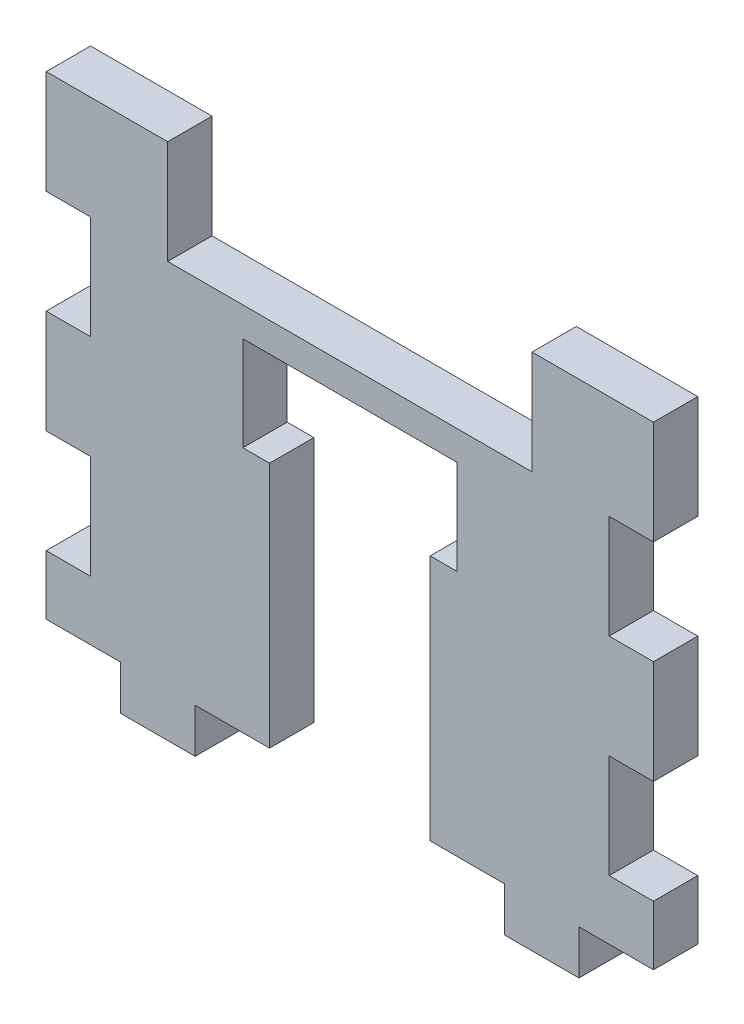
SolidWorks part; units mm, degrees
ref_plane "Front Plane" through (0, 0, 0) normal (0, 0, 1) x (1, 0, 0)
ref_plane "Top Plane" through (0, 0, 0) normal (0, 1, 0) x (1, 0, 0)
ref_plane "Right Plane" through (0, 0, 0) normal (1, 0, 0) x (0, 0, -1)
sketch "Sketch1" plane through (0, 0, 0) normal (0, 0, 1) x (1, 0, 0)
  line L0 (0, 0.2997) -> (31.2293, 0.2997) construction
  line L1 (-31.2293, -26.67) -> (31.2293, -26.67) construction
  line L2 (-31.2293, -26.67) -> (-31.2293, 26.67)
  line L3 (-31.2293, 26.67) -> (31.2293, 26.67)
  line L4 (31.2293, -26.67) -> (31.2293, 26.67)
  line L5 (-31.2293, -26.67) -> (31.2293, 26.67) construction
  line L6 (-31.2293, 26.67) -> (31.2293, -26.67) construction
  line L7 (0, 26.67) -> (0, 0.2997) construction
  line L8 (-31.2293, 26.67) -> (-31.2293, 7.8308) construction
  line L9 (0, 26.67) -> (0, 12.9921) construction
  line L10 (31.2293, 26.67) -> (26.67, 26.67) construction
  line L11 (26.67, 26.67) -> (26.67, -26.67) construction
  line L12 (0, 12.9921) -> (26.67, 12.9921) construction
  line L13 (0, 12.9921) -> (11.0096, 12.9921) construction
  line L14 (11.0096, 12.9921) -> (11.0096, 3.2715)
  line L15 (11.0096, 3.2715) -> (8.2572, 3.2715)
  line L16 (11.0096, 12.9921) -> (-11.0096, 12.9921)
  line L17 (8.2572, 3.2715) -> (8.2572, -26.67)
  line L18 (-11.0096, 12.9921) -> (-11.0096, 3.2715)
  line L19 (8.2572, -26.67) -> (31.2293, -26.67)
  line L20 (-11.0096, 3.2715) -> (-8.2572, 3.2715)
  line L21 (-8.2572, 3.2715) -> (-8.2572, -26.67)
  line L22 (-8.2572, -26.67) -> (-31.2293, -26.67)
  line L23 (15.9146, -22.1107) -> (8.2572, -22.1107)
  line L24 (-31.2293, 26.67) -> (-26.67, 26.67) construction
  line L25 (-31.2293, 26.67) -> (-31.2293, 16.002) construction
  line L26 (-31.2293, 16.002) -> (-26.67, 16.002) construction
  line L27 (-26.67, 26.67) -> (-26.67, 16.002) construction
  line L28 (-26.67, 16.002) -> (-31.2293, 16.002)
  line L29 (-26.67, 16.002) -> (-26.67, 5.334)
  line L30 (-26.67, 5.334) -> (-31.2293, 5.334)
  line L31 (-31.2293, 16.002) -> (-31.2293, 5.334)
  line L32 (-26.67, 5.334) -> (-31.2293, 5.334) construction
  line L33 (-26.67, 5.334) -> (-26.67, -5.334) construction
  line L34 (-26.67, -5.334) -> (-31.2293, -5.334) construction
  line L35 (-31.2293, 5.334) -> (-31.2293, -5.334) construction
  line L36 (-26.67, -5.334) -> (-31.2293, -5.334)
  line L37 (-26.67, -5.334) -> (-26.67, -16.002)
  line L38 (-26.67, -16.002) -> (-31.2293, -16.002)
  line L39 (-31.2293, -5.334) -> (-31.2293, -16.002)
  line L40 (-26.67, -16.002) -> (-31.2293, -16.002) construction
  line L41 (-26.67, -16.002) -> (-26.67, -26.67) construction
  line L42 (-26.67, -26.67) -> (-31.2293, -26.67) construction
  line L43 (-31.2293, -16.002) -> (-31.2293, -26.67) construction
  line L44 (31.2293, 26.67) -> (26.67, 26.67) construction
  line L45 (31.2293, 26.67) -> (31.2293, 16.002) construction
  line L46 (31.2293, 16.002) -> (26.67, 16.002) construction
  line L47 (26.67, 26.67) -> (26.67, 16.002) construction
  line L48 (26.67, 16.002) -> (31.2293, 16.002)
  line L49 (26.67, 16.002) -> (26.67, 5.334)
  line L50 (26.67, 5.334) -> (31.2293, 5.334)
  line L51 (31.2293, 16.002) -> (31.2293, 5.334)
  line L52 (26.67, 5.334) -> (31.2293, 5.334) construction
  line L53 (26.67, 5.334) -> (26.67, -5.334) construction
  line L54 (26.67, -5.334) -> (31.2293, -5.334) construction
  line L55 (31.2293, 5.334) -> (31.2293, -5.334) construction
  line L56 (26.67, -5.334) -> (31.2293, -5.334)
  line L57 (26.67, -5.334) -> (26.67, -16.002)
  line L58 (26.67, -16.002) -> (31.2293, -16.002)
  line L59 (31.2293, -5.334) -> (31.2293, -16.002)
  line L60 (26.67, -16.002) -> (31.2293, -16.002) construction
  line L61 (26.67, -16.002) -> (26.67, -26.67) construction
  line L62 (26.67, -26.67) -> (31.2293, -26.67) construction
  line L63 (31.2293, -16.002) -> (31.2293, -26.67) construction
  line L64 (-31.2293, 26.67) -> (-18.7376, 26.67) construction
  line L65 (-31.2293, 26.67) -> (-31.2293, 22.1107) construction
  line L66 (-31.2293, 22.1107) -> (-18.7376, 22.1107) construction
  line L67 (-18.7376, 26.67) -> (-18.7376, 22.1107) construction
  line L68 (-18.7376, 22.1107) -> (-6.2459, 22.1107) construction
  line L69 (-18.7376, 22.1107) -> (-18.7376, 26.67)
  line L70 (-18.7376, 26.67) -> (-6.2459, 26.67)
  line L72 (-6.2459, 22.1107) -> (6.2459, 22.1107) construction
  line L73 (-6.2459, 22.1107) -> (-6.2459, 26.67) construction
  line L74 (-6.2459, 26.67) -> (6.2459, 26.67) construction
  line L75 (6.2459, 22.1107) -> (6.2459, 26.67) construction
  line L76 (6.2459, 22.1107) -> (18.7376, 22.1107) construction
  line L78 (6.2459, 26.67) -> (18.7376, 26.67)
  line L79 (18.7376, 22.1107) -> (18.7376, 26.67)
  line L80 (18.7376, 22.1107) -> (31.2293, 22.1107) construction
  line L81 (18.7376, 22.1107) -> (18.7376, 26.67) construction
  line L82 (18.7376, 26.67) -> (31.2293, 26.67) construction
  line L83 (31.2293, 22.1107) -> (31.2293, 26.67) construction
  line L84 (-31.2293, -26.67) -> (-23.5719, -26.67) construction
  line L85 (-31.2293, -26.67) -> (-31.2293, -22.1107) construction
  line L86 (-31.2293, -22.1107) -> (-23.5719, -22.1107)
  line L87 (-23.5719, -26.67) -> (-23.5719, -22.1107)
  line L88 (-23.5719, -22.1107) -> (-15.9146, -22.1107) construction
  line L89 (-23.5719, -22.1107) -> (-23.5719, -26.67) construction
  line L90 (-23.5719, -26.67) -> (-15.9146, -26.67) construction
  line L91 (-15.9146, -22.1107) -> (-15.9146, -26.67)
  line L92 (-15.9146, -22.1107) -> (-8.2572, -22.1107)
  line L93 (-15.9146, -22.1107) -> (-15.9146, -26.67) construction
  line L94 (-15.9146, -26.67) -> (-8.2572, -26.67) construction
  line L95 (-8.2572, -22.1107) -> (-8.2572, -26.67) construction
  line L96 (15.9146, -22.1107) -> (15.9146, -26.67)
  line L97 (23.5719, -26.67) -> (23.5719, -22.1107)
  line L98 (31.2293, -22.1107) -> (23.5719, -22.1107)
  line L99 (-6.2459, 22.1107) -> (6.2459, 22.1107) construction
  line L100 (26.67, 16.002) -> (-26.67, 16.002) construction
  line L101 (-18.7376, 22.1107) -> (-18.7376, 16.002)
  line L102 (18.7376, 22.1107) -> (18.7376, 16.002)
  line L103 (18.7376, 16.002) -> (-18.7376, 16.002)
  point P0 (0, 0)
  dimension "D1" = 62.4586
  dimension "D2" = 53.34
  dimension "D4" = 26.3703
  dimension "D3" = 18.8392
  dimension "D5" = 13.6779
  dimension "D6" = 4.5593
  dimension "D7" = 11.0096
  dimension "D8" = 9.7206
  dimension "D9" = 2.7524
  dimension "D10" = 4.5593
  dimension "D11" = 4.5593
  dimension "D12" = 4.5593
extrude "Boss-Extrude1" add sketch "Sketch1" along normal blind 4.5593
equation "\"D1@Sketch1\"=\"max32_width\" + (\"material_width\"*2)"
equation "\"D2@Sketch1\"=\"neck_height\""
equation "\"material_width\" = 0.1795"
equation "\"max32_width\" = 2.1"
equation "\"max32_length\" = 4.0"
equation "\"max32_hole_diameter\" = 0.12"
equation "\"max32_dist2hole_width\" = 0.1"
equation "\"max32_dist2hole1_length\" = 0.6"
equation "\"max32_dist2hole2_length\" = 3.8"
equation "\"head_height\" = 2.0"
equation "\"neck_height\" = \"max32_width\""
equation "\"washer_height\" = 0.1"
equation "\"wall_length\" = 3.5"
equation "\"wall_height\" = 1.5"
equation "\"extra_space\" = 0.25"
equation "\"arc_radius\" = \"wall_length\" + \"washer_height\" + \"neck_height\" + (\"head_height\"/2)"
equation "\"arc_wall_height\" = \"arc_radius\" + \"wall_length\" + \"extra_space\""
equation "\"foot_length\" = 1.0"
equation "\"peg_diameter\" = 0.2475"
equation "\"barring_diameter\" = 0.8657"
equation "\"imu_space\" = 0.8"
equation "\"encoder_height\" = 0.8587"
equation "\"encoder_sub_height\" = 0.3827"
equation "\"encoder_length\" = 1.1043"
equation "\"encoder_sub_length\" = 0.5886"
equation "\"encoder_width\" = 0.8669"
equation "\"D4@Sketch1\"=\"material_width\" +\"encoder_height\""
equation "\"D3@Sketch1\"=\"encoder_sub_height\" + (\"material_width\"*2)"
equation "\"D5@Sketch1\"=\"material_width\"*3"
equation "\"D6@Sketch1\"=\"material_width\""
equation "\"D7@Sketch1\"=\"encoder_width\"/2"
equation "\"D8@Sketch1\"=\"encoder_sub_height\""
equation "\"D9@Sketch1\"=\"encoder_width\"/8"
equation "\"D10@Sketch1\"=\"material_width\""
equation "\"D11@Sketch1\"=\"material_width\""
equation "\"D1@Boss-Extrude1\"=\"material_width\""
equation "\"D12@Sketch1\"=\"material_width\""
